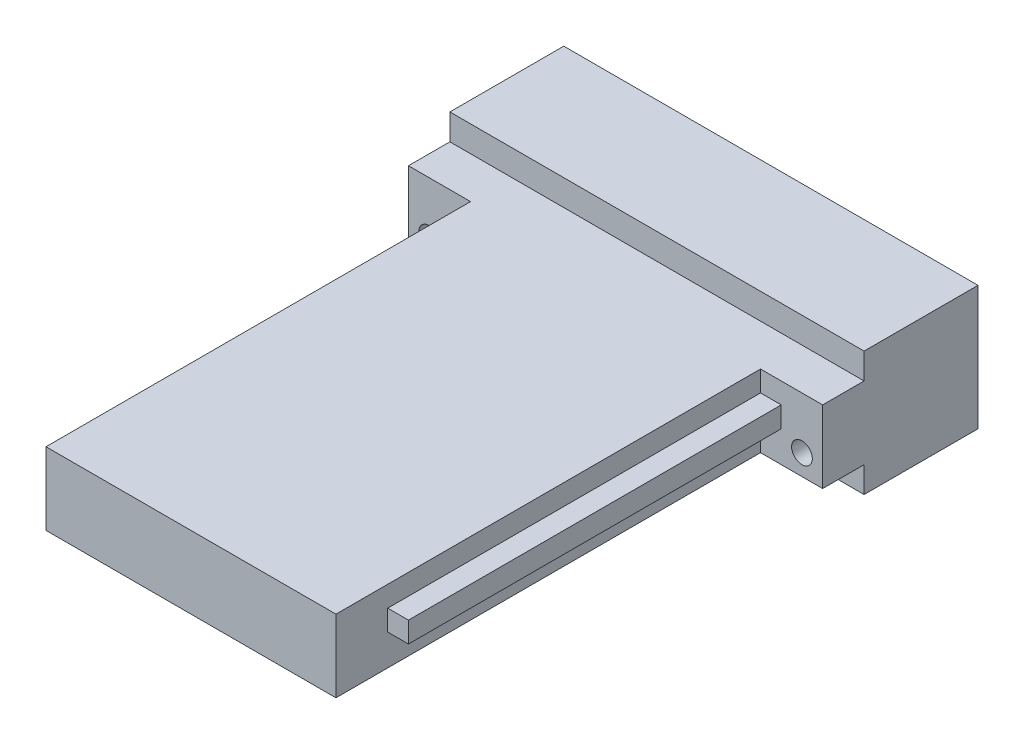
SolidWorks part; units mm, degrees
material "Polylactide (PLA)"
ref_plane "Front Plane" through (0, 0, 0) normal (0, 0, 1) x (1, 0, 0)
ref_plane "Top Plane" through (0, 0, 0) normal (0, 1, 0) x (1, 0, 0)
ref_plane "Right Plane" through (0, 0, 0) normal (1, 0, 0) x (0, 0, -1)
sketch "Sketch1" plane through (0, 0, 0) normal (0, 1, 0) x (1, 0, 0)
  line L1 (0, 0) -> (28, 0)
  line L2 (0, 0) -> (0, 45)
  line L3 (0, 45) -> (28, 45)
  line L4 (28, 0) -> (28, 45)
extrude "Boss-Extrude1" add sketch "Sketch1" along normal blind 7 contours L2 L3 L4 L1
sketch "Sketch4" plane through (28, 0, 0) normal (1, 0, 0) x (0, 0, -1)
  line L1 (45, 0) -> (41, 0)
  line L2 (45, 0) -> (45, 12)
  line L3 (45, 12) -> (41, 12)
  line L4 (41, 0) -> (41, 12)
sketch "Sketch6" plane through (0, 0, 0) normal (-1, 0, 0) x (0, 0, 1)
  line L0 (0, 7) -> (-45, 7) construction
  line L1 (-45, 7) -> (-41, 7)
  line L2 (-45, 7) -> (-45, 0)
  line L3 (-45, 0) -> (-41, 0)
  line L4 (-41, 7) -> (-41, 0)
sketch "Sketch7" plane through (28, 0, 0) normal (1, 0, 0) x (0, 0, -1)
  line L1 (45, 0) -> (41, 0)
  line L2 (45, 0) -> (45, 7)
  line L3 (45, 7) -> (41, 7)
  line L4 (41, 0) -> (41, 7)
extrude "Boss-Extrude2" add sketch "Sketch7" along normal blind 6
extrude "Boss-Extrude3" add sketch "Sketch6" along normal blind 6 contours L4 L3 L2 L1
sketch "Sketch10" plane through (0, 0, -41) normal (0, 0, 1) x (1, 0, 0)
  line L1 (-6, 0) -> (-4, 0)
  line L2 (-6, 0) -> (-6, 2)
  line L3 (-6, 2) -> (-4, 2)
  line L4 (-4, 0) -> (-4, 2)
  line L5 (34, 0) -> (32, 0)
  line L6 (34, 0) -> (34, 2)
  line L7 (34, 2) -> (32, 2)
  line L8 (32, 0) -> (32, 2)
  circle A0 centre (-4, 2) radius 1
  circle A1 centre (32, 2) radius 1
extrude "Cut-Extrude1" cut sketch "Sketch10" against normal blind 6 contours A1 | A0
sketch "Sketch11" plane through (0, 0, -45) normal (0, 0, -1) x (-1, 0, 0)
  line L0 (-28, 0) -> (-28, 12) construction
  line L9 (-28, 0) -> (-26, 0)
  line L10 (-28, 0) -> (-28, 1)
  line L11 (-28, 1) -> (-26, 1)
  line L12 (-26, 0) -> (-26, 1)
  line L13 (-28, 0) -> (-28, 12) construction
  line L14 (6, 7) -> (-34, 7) construction
  line L15 (-26, 1) -> (-2, 1)
  line L16 (-26, 1) -> (-26, 6)
  line L17 (-26, 6) -> (-2, 6)
  line L18 (-2, 1) -> (-2, 6)
  line L19 (-26, 6) -> (-2, 6)
  line L20 (-26, 6) -> (-26, 1)
  line L21 (-26, 1) -> (-2, 1)
  line L22 (-2, 6) -> (-2, 1)
  line L23 (-34, 0) -> (-34, 7) construction
extrude "Cut-Extrude2" cut sketch "Sketch11" against normal blind 43 contours L16 L17 L18 L15
sketch "Sketch16" plane through (0, 0, 0) normal (-1, 0, 0) x (0, 0, 1)
  line L0 (-41, 7) -> (-41, 5)
  line L1 (-41, 0) -> (-41, 12) construction
  line L3 (-41, 5) -> (-5, 5)
  line L4 (-41, 5) -> (-41, 3)
  line L5 (-41, 3) -> (-5, 3)
  line L6 (-5, 5) -> (-5, 3)
extrude "Boss-Extrude7" add sketch "Sketch16" along normal blind 2 contours L3 L6 L5 L4
sketch "Sketch17" plane through (28, 0, 0) normal (1, 0, 0) x (0, 0, -1)
  line L0 (41, 7) -> (41, 5)
  line L1 (41, 0) -> (41, 12) construction
  line L3 (41, 5) -> (5, 5)
  line L4 (41, 5) -> (41, 3)
  line L5 (41, 3) -> (5, 3)
  line L6 (5, 5) -> (5, 3)
extrude "Boss-Extrude8" add sketch "Sketch17" along normal blind 2 contours L3 L6 L5 L4
sketch "Sketch30" plane through (0, 0, -45) normal (0, 0, -1) x (-1, 0, 0)
  line L5 (-34, 9.5) -> (6, 9.5)
  line L6 (-34, 9.5) -> (-34, -2.5)
  line L7 (-34, -2.5) -> (6, -2.5)
  line L8 (6, 9.5) -> (6, -2.5)
  dimension "D2" = 12
extrude "Boss-Extrude13" add sketch "Sketch30" along normal blind 11
sketch "Sketch31" plane through (0, 0, -56) normal (0, 0, -1) x (-1, 0, 0)
  line L5 (-26, 8.5) -> (-2, 8.5)
  line L6 (-26, 8.5) -> (-26, -1.5)
  line L7 (-26, -1.5) -> (-2, -1.5)
  line L8 (-2, 8.5) -> (-2, -1.5)
  dimension "D3" = 10
  dimension "D4" = 24
extrude "Cut-Extrude11" cut sketch "Sketch31" against normal blind 10
sketch "Sketch32" plane through (0, 0, -46) normal (0, 0, -1) x (-1, 0, 0)
  line L0 (-2, -1.5) -> (-2, 8.5) construction
  line L5 (-26, 6) -> (-2, 6)
  line L6 (-26, 6) -> (-26, 1)
  line L7 (-26, 1) -> (-2, 1)
  line L8 (-2, 6) -> (-2, 1)
  dimension "D2" = 5
extrude "Cut-Extrude12" cut sketch "Sketch32" against normal blind 1
sketch "Sketch33" plane through (0, 0, -45) normal (0, 0, 1) x (1, 0, 0)
  circle A0 centre (32, 2) radius 1
extrude "Cut-Extrude13" cut sketch "Sketch33" against normal blind 11
sketch "Sketch34" plane through (0, 0, -45) normal (0, 0, 1) x (1, 0, 0)
  circle A0 centre (-4, 2) radius 1
extrude "Cut-Extrude14" cut sketch "Sketch34" against normal blind 11
